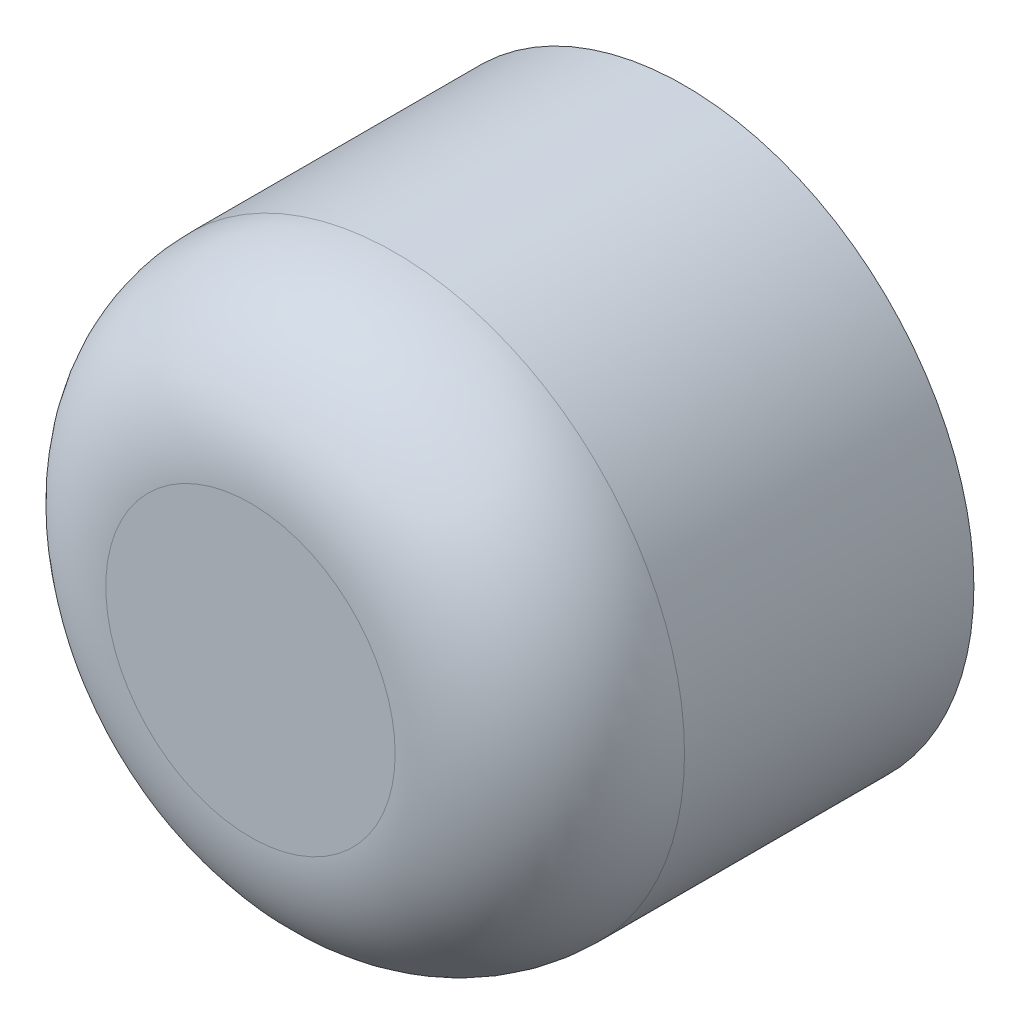
SolidWorks part; units mm, degrees
material "ABS"
ref_plane "Front Plane" through (0, 0, 0) normal (0, 0, 1) x (1, 0, 0)
ref_plane "Top Plane" through (0, 0, 0) normal (0, 1, 0) x (1, 0, 0)
ref_plane "Right Plane" through (0, 0, 0) normal (1, 0, 0) x (0, 0, -1)
sketch "Sketch2" plane through (0, 0, 0) normal (0, 0, 1) x (1, 0, 0)
  circle A1 centre (0, 0) radius 50.8
  dimension "D1" = 101.6
extrude "Boss-Extrude1" add sketch "Sketch2" along normal blind 76.2
fillet "Fillet1" radius 25.4 1 edges at (50.8, 0, 76.2)
